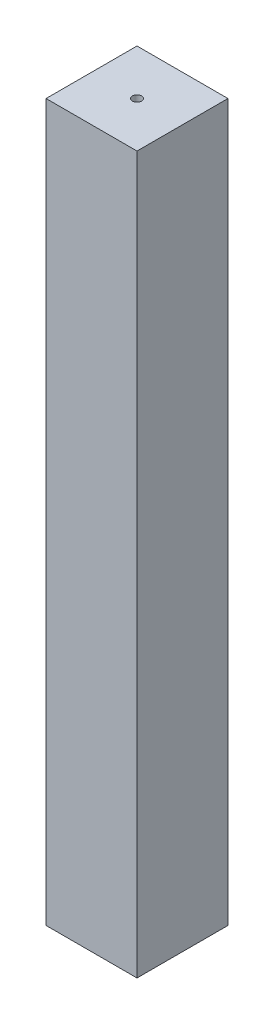
SolidWorks part; units mm, degrees
ref_plane "Front Plane" through (0, 0, 0) normal (0, 0, 1) x (1, 0, 0)
ref_plane "Top Plane" through (0, 0, 0) normal (0, 1, 0) x (1, 0, 0)
ref_plane "Right Plane" through (0, 0, 0) normal (1, 0, 0) x (0, 0, -1)
sketch "Sketch1" plane through (0, 0, 0) normal (0, 1, 0) x (1, 0, 0)
  line L1 (-25.4, 25.4) -> (25.4, 25.4)
  line L2 (-25.4, 25.4) -> (-25.4, -25.4)
  line L3 (-25.4, -25.4) -> (25.4, -25.4)
  line L4 (25.4, 25.4) -> (25.4, -25.4)
  line L5 (-25.4, 25.4) -> (25.4, -25.4) construction
  line L6 (-25.4, -25.4) -> (25.4, 25.4) construction
  point P0 (0, 0)
  dimension "Length" = 50.8
  dimension "Width" = 50.8
extrude "Boss-Extrude1" add sketch "Sketch1" along normal blind 400.05
hole_wizard "#10 Clearance Hole1" positions "Sketch3" profile "Sketch2" hole size "#10" standard "ANSI Inch"
sketch "Sketch3" plane through (0, 400.05, 0) normal (0, 1, 0) x (1, 0, 0)
  point P0 (0, 0)
sketch "Sketch2" plane through (0, 400.05, 0) normal (1, 0, 0) x (0, 0, 1)
  line L0 (0, 0) -> (0, 26.9338)
  line L1 (0, 26.9338) -> (2.5527, 25.4)
  line L2 (2.5527, 25.4) -> (2.5527, 0)
  line L5 (2.5527, 0) -> (0, 0)
  line L10 (0, 26.9338) -> (-2.5527, 25.4) construction
  line L11 (0, -6.35) -> (0, 107.95) construction
  dimension "Hole Dia." = 5.1054
  dimension "Hole Depth" = 25.4
  dimension "Drill Angle" = 118
